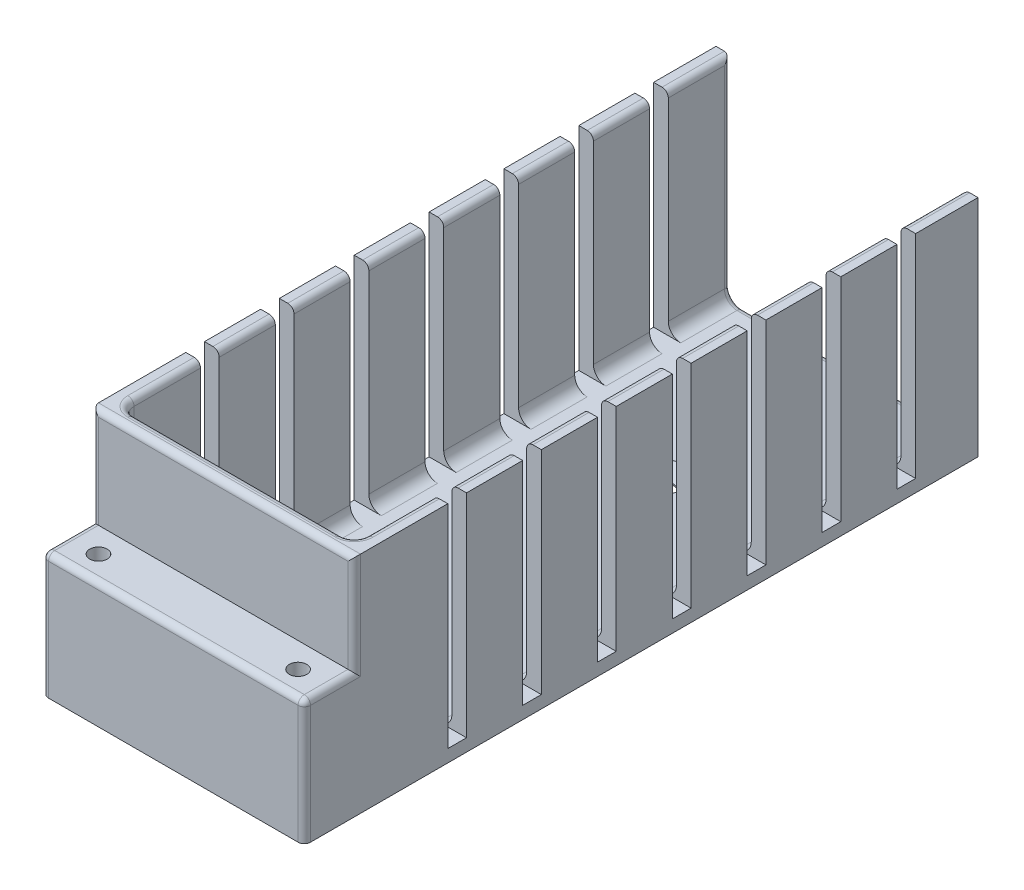
SolidWorks part; units mm, degrees
ref_plane "Front Plane" through (0, 0, 0) normal (0, 0, 1) x (1, 0, 0)
ref_plane "Top Plane" through (0, 0, 0) normal (0, 1, 0) x (1, 0, 0)
ref_plane "Right Plane" through (0, 0, 0) normal (1, 0, 0) x (0, 0, -1)
sketch "Sketch1" plane through (0, 0, 0) normal (0, 1, 0) x (1, 0, 0)
  line L1 (-21, -50) -> (21, -50)
  line L2 (-21, -50) -> (-21, 50)
  line L3 (-21, 50) -> (21, 50)
  line L4 (21, -50) -> (21, 50)
  line L5 (-21, -50) -> (21, 50) construction
  line L6 (-21, 50) -> (21, -50) construction
  point P0 (0, 0)
  dimension "D1" = 42
  dimension "D2" = 100
extrude "Boss-Extrude1" add sketch "Sketch1" along normal blind 2
sketch "Sketch2" plane through (0, 2, 0) normal (0, 1, 0) x (1, 0, 0)
  line L0 (-21, 50) -> (-18.65, 50)
  line L1 (21, 50) -> (-21, 50) construction
  line L2 (-18.65, 50) -> (-18.65, -47.65)
  line L3 (-18.65, -47.65) -> (18.65, -47.65)
  line L4 (21, -50) -> (21, 50)
  line L5 (21, 50) -> (-21, 50)
  line L6 (-21, 50) -> (-21, -50)
  line L7 (-21, -50) -> (21, -50)
  line L8 (21, -50) -> (21, 50)
  line L10 (-21, 50) -> (-21, -50)
  line L11 (-21, -50) -> (21, -50)
  line L12 (18.65, -47.65) -> (18.65, 50)
  line L13 (18.65, 50) -> (21, 50)
  line L14 (0, -47.65) -> (0, 0) construction
  line L15 (0, -47.65) -> (0, -50) construction
  dimension "D2" = 37.3
  dimension "D1" = 0
extrude "Boss-Extrude2" add sketch "Sketch2" along normal blind 34
fillet "Fillet1" radius 2 5 edges at (18.65, 2, -1.175) (0, 2, 47.65) (-18.65, 2, -1.175) (18.65, 19, 47.65) (-18.65, 19, 47.65)
sketch "Sketch3" plane through (0, 36, 0) normal (0, 1, 0) x (1, 0, 0)
  line L0 (-21, 50) -> (-21, -50) construction
  line L1 (-21, 40) -> (21, 40)
  line L2 (-21, 40) -> (-21, 37)
  line L3 (-21, 37) -> (21, 37)
  line L4 (21, 40) -> (21, 37)
  line L5 (21, -50) -> (21, 50) construction
  line L6 (21, 50) -> (18.65, 50) construction
  dimension "D1" = 10
  dimension "D2" = 3
extrude "Cut-Extrude1" cut sketch "Sketch3" against normal up to surface (34 mm away) up to face at (0, 2, -2.175)
pattern_linear "LPattern1" count 7 spacing 12 along (0, 0, 1) of "Cut-Extrude1"
sketch "Sketch4" plane through (0, 2, 0) normal (0, 1, 0) x (1, 0, 0)
  circle A0 centre (0.5607, 20) radius 1.4 construction
  circle A1 centre (0.5607, 20) radius 1.4 construction
  circle A2 centre (0.5607, -20) radius 1.4 construction
  circle A3 centre (0.5607, -20) radius 1.4 construction
hole_wizard "CSK for M3 Flat Head Machine Screw1" positions "3DSketch1" profile "Sketch5" countersink size "M3" standard "ANSI Metric" end condition through all
sketch3d "3DSketch1"
  point P0 (0.5607, 2, -20)
  point P3 (0.5607, 2, 20)
sketch "Sketch5" plane through (0.5607, 2, -20) normal (1, 0, 0) x (0, 0, 1)
  line L0 (0, 0) -> (0, 2)
  line L1 (0, 2) -> (1.6, 2)
  line L2 (1.6, 2) -> (1.6, 1.775)
  line L3 (1.6, 1.775) -> (3.375, 0)
  line L5 (3.375, 0) -> (0, 0)
  line L6 (-1.6, 1.775) -> (-3.375, 0) construction
  line L11 (0, -6.35) -> (0, 107.95) construction
  dimension "Thru Hole Dia." = 3.2
  dimension "Thru Hole Depth" = 2
  dimension "Near C'Sink Dia." = 6.75
  dimension "Near C'Sink Angle" = 90
sketch "Sketch7" plane through (0, 0, 0) normal (0, -1, 0) x (1, 0, 0)
  line L0 (-21, 50) -> (-21, 58)
  line L1 (-21, 58) -> (21, 58)
  line L2 (21, 58) -> (21, 50)
  line L3 (21, 50) -> (-21, 50)
  line L4 (-16, 54) -> (16, 54) construction
  circle A0 centre (-16, 54) radius 1.4
  circle A1 centre (16, 54) radius 1.4
  point P7 (21, 62.9352)
  dimension "D1" = 2.8
  dimension "D2" = 5
  dimension "D3" = 5
  dimension "D4" = 4
  dimension "D5" = 8
extrude "Boss-Extrude3" add sketch "Sketch7" against normal blind 20
fillet "Fillet2" radius 1 32 edges at (18.65, 36, 40.325) (18.0642, 36, 47.0642) (-18.65, 36, 40.325) (-18.0642, 36, 47.0642) (0, 36, 47.65) (18.65, 36, -45) (18.65, 36, -32.5) (18.65, 36, -20.5) (18.65, 36, -8.5) (18.65, 36, 3.5) (-18.65, 36, 3.5) (-18.65, 36, -8.5) (-18.65, 36, -20.5) (-18.65, 36, -32.5) (-18.65, 36, -45) (18.65, 36, 27.5) (18.65, 36, 15.5) (-18.65, 36, 15.5) (-18.65, 36, 27.5) (21, 28, 50) (-21, 28, 50) (18.65, 20, -50) (18.0642, 2.5858, -50) (-18.65, 20, -50) (-18.0642, 2.5858, -50) (0, 2, -50) (0, 36, 50) (-21, 20, 54) (21, 20, 54) (21, 10, 58) (-21, 10, 58) (0, 20, 58)
